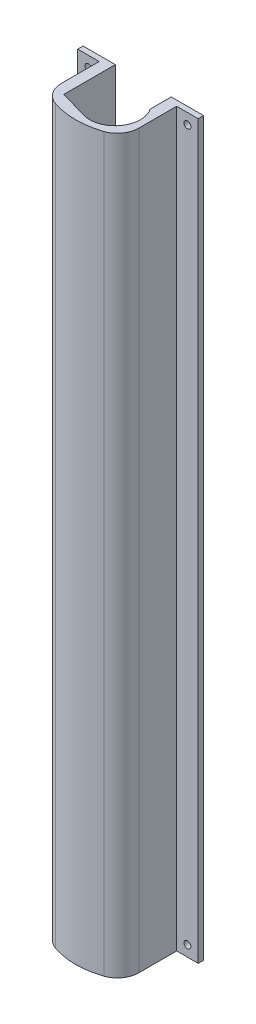
SolidWorks part; units mm, degrees
ref_plane "Front Plane" through (0, 0, 0) normal (0, 0, 1) x (1, 0, 0)
ref_plane "Top Plane" through (0, 0, 0) normal (0, 1, 0) x (1, 0, 0)
ref_plane "Right Plane" through (0, 0, 0) normal (1, 0, 0) x (0, 0, -1)
sketch "Sketch1" plane through (0, 0, 0) normal (0, 1, 0) x (1, 0, 0)
  line L0 (-20.574, -9.6521) -> (-4.162, -14.3967)
  line L1 (-4.1621, 14.3967) -> (-20.574, 9.652) construction
  line L2 (-20.574, 9.652) -> (-20.574, -9.6521)
  line L3 (-39.624, 20.7467) -> (-20.574, 20.7467)
  line L4 (-39.624, 20.7467) -> (-39.624, 17.5717)
  line L6 (12.446, 20.7467) -> (31.496, 20.7467)
  line L7 (-39.624, 17.5717) -> (-26.924, 17.5717)
  line L9 (-26.924, 17.5717) -> (-26.924, -12.8271)
  line L10 (31.496, 20.7467) -> (31.496, 17.5717)
  line L11 (31.496, 17.5717) -> (18.796, 17.5717)
  line L12 (18.796, 17.5717) -> (18.796, -12.8271)
  line L13 (-20.574, 9.652) -> (-20.574, 20.7467)
  line L14 (12.446, 20.7467) -> (12.446, 8.3478)
  arc A0 (-4.162, -14.3967) -> (12.446, 8.3478) centre (0, 0) ccw
  arc A1 (-26.924, -12.8271) -> (18.796, -12.8271) centre (-4.064, 25.294) ccw
  arc A2 (12.446, 8.3478) -> (-4.1621, 14.3967) centre (0, 0) ccw construction
  point P6 (12.446, 14.5473)
  point P16 (21.971, 20.7467)
  dimension "D2" = 14.9863
  dimension "D14" = 6.35
  dimension "D10" = 44.45
  dimension "D1" = 19.3041
  dimension "D3" = 16.4119
  dimension "D4" = 106.124
  dimension "D5" = 20.574
  dimension "D6" = 106.125
  dimension "D7" = 6.35
  dimension "D8" = 6.35
  dimension "D9" = 3.175
  dimension "D11" = 12.7
  dimension "D12" = 3.175
  dimension "D13" = 33.02
extrude "Boss-Extrude1" add sketch "Sketch1" along normal blind 431.8
sketch "Sketch2" plane through (0, 0, -17.5717) normal (0, 0, 1) x (1, 0, 0)
  line L0 (-39.624, 0) -> (-26.924, 0) construction
  line L1 (-39.624, 431.8) -> (-39.624, 0) construction
  line L2 (-39.624, 431.8) -> (-26.924, 431.8) construction
  line L3 (31.496, 431.8) -> (31.496, 0) construction
  circle A0 centre (-33.274, 425.45) radius 2.032
  circle A1 centre (-33.274, 6.35) radius 2.032
  circle A2 centre (25.146, 425.45) radius 2.032
  circle A3 centre (25.146, 6.35) radius 2.032
  dimension "D5" = 4.064
  dimension "D1" = 6.35
  dimension "D2" = 6.35
  dimension "D3" = 6.35
  dimension "D4" = 6.35
extrude "Cut-Extrude1" cut sketch "Sketch2" against normal through all
fillet "Fillet2" radius 12.7 2 edges at (18.796, 215.9, 12.8271) (-26.924, 215.9, 12.8271)
scale "Scale1" scale about centroid uniform scaling yes scale factor 0.25
